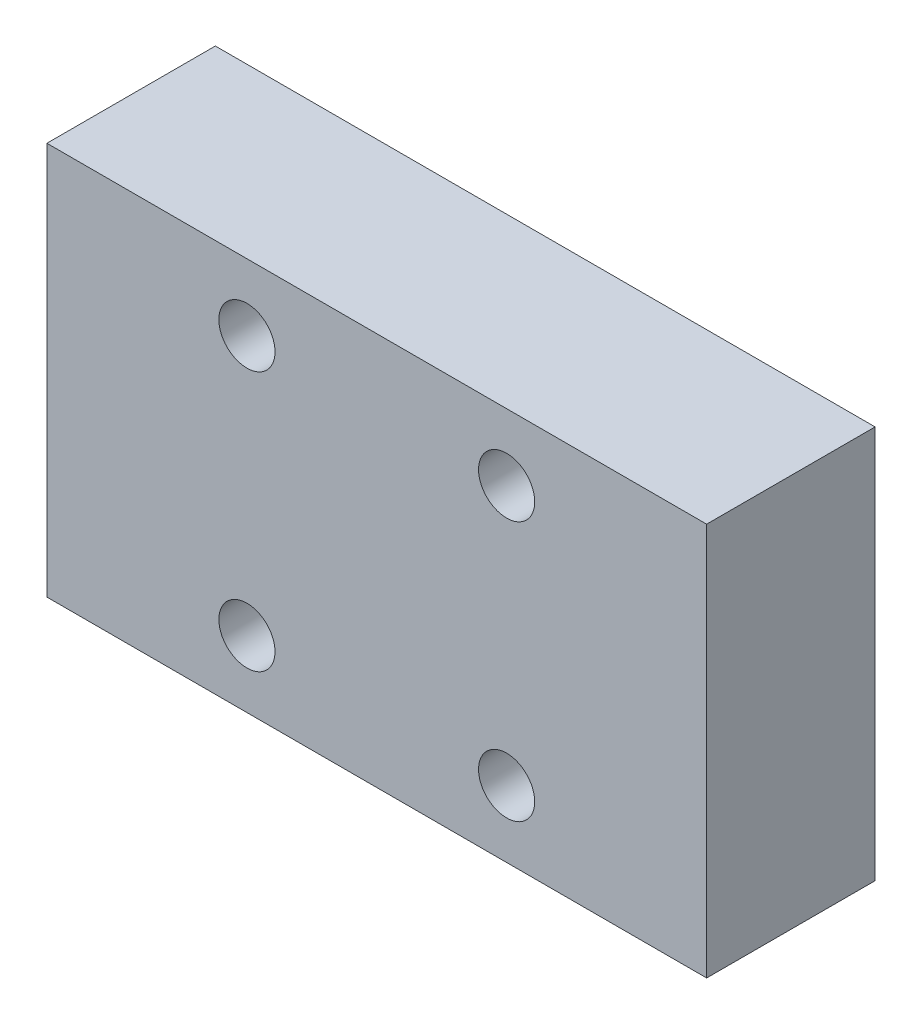
SolidWorks part; units mm, degrees
material "自定义塑料"
ref_plane "前视基准面" through (0, 0, 0) normal (0, 0, 1) x (1, 0, 0)
ref_plane "上视基准面" through (0, 0, 0) normal (0, 1, 0) x (1, 0, 0)
ref_plane "右视基准面" through (0, 0, 0) normal (1, 0, 0) x (0, 0, -1)
sketch "草图1" plane through (0, 0, 0) normal (0, 0, 1) x (1, 0, 0)
  line L1 (-33.9416, 36.5693) -> (13.0584, 36.5693)
  line L2 (-33.9416, 36.5693) -> (-33.9416, 8.5693)
  line L3 (-33.9416, 8.5693) -> (13.0584, 8.5693)
  line L4 (13.0584, 36.5693) -> (13.0584, 8.5693)
  dimension "D1" = 47
  dimension "D2" = 28
extrude "凸台-拉伸1" add sketch "草图1" along normal blind 12 contours L1 L4 L3 L2
sketch "草图2" plane through (0, 0, 12) normal (0, 0, 1) x (1, 0, 0)
  line L0 (-10.4416, 36.5693) -> (-10.4416, -3.0542) construction
  line L1 (-33.9416, 36.5693) -> (13.0584, 36.5693) construction
  line L2 (-33.9416, 22.5693) -> (13.0584, 22.5693) construction
  line L3 (-33.9416, 36.5693) -> (-33.9416, 8.5693) construction
  line L4 (13.0584, 36.5693) -> (13.0584, 8.5693) construction
  circle A0 centre (-19.6916, 31.8193) radius 2
  circle A1 centre (-1.1916, 31.8193) radius 2
  circle A2 centre (-1.1916, 13.3193) radius 2
  circle A3 centre (-19.6916, 13.3193) radius 2
  dimension "D1" = 4
  dimension "D2" = 18.5
  dimension "D3" = 18.5
extrude "切除-拉伸1" cut sketch "草图2" against normal blind 12
